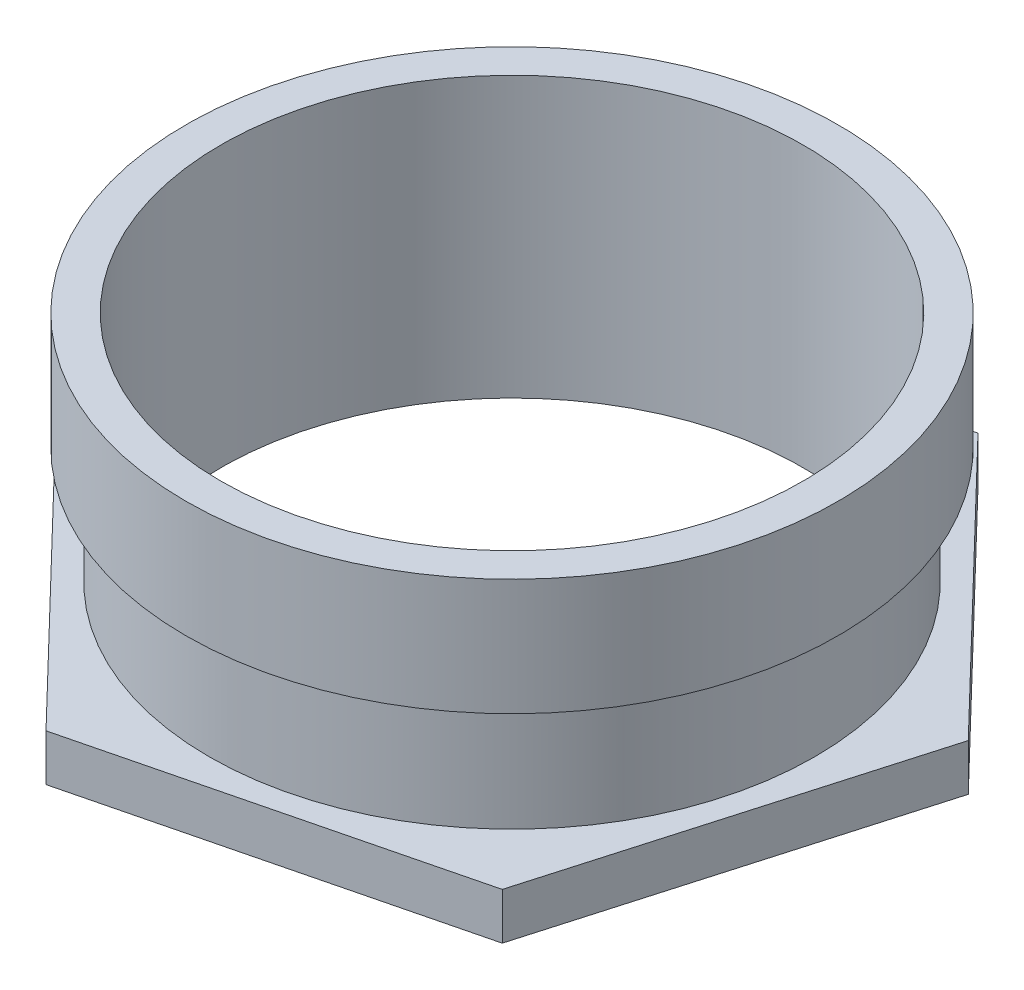
SolidWorks part; units mm, degrees
ref_plane "前基準面" through (0, 0, 0) normal (0, 0, 1) x (1, 0, 0)
ref_plane "上基準面" through (0, 0, 0) normal (0, 1, 0) x (1, 0, 0)
ref_plane "右基準面" through (0, 0, 0) normal (1, 0, 0) x (0, 0, -1)
sketch "草圖1" plane through (0, 0, 0) normal (0, 1, 0) x (1, 0, 0)
  line L0 (-4.469, -15.5358) -> (11.2199, -11.6382)
  line L6 (11.2199, -11.6382) -> (15.6889, 3.8977)
  line L7 (15.6889, 3.8977) -> (4.469, 15.5358)
  line L8 (4.469, 15.5358) -> (-11.2199, 11.6382)
  line L9 (-11.2199, 11.6382) -> (-15.6889, -3.8977)
  line L10 (-15.6889, -3.8977) -> (-4.469, -15.5358)
  circle A0 centre (0, 0) radius 14 construction
  circle A1 centre (0, 0) radius 12.5
  dimension "D1" = 25
extrude "填料-伸長1" add sketch "草圖1" along normal blind 2
sketch "草圖2" plane through (0, 2, 0) normal (0, 1, 0) x (1, 0, 0)
  circle A0 centre (0, 0) radius 12.5
  circle A1 centre (0, 0) radius 13
  dimension "D1" = 26
extrude "填料-伸長2" add sketch "草圖2" along normal blind 5
sketch "草圖3" plane through (0, 7, 0) normal (0, 1, 0) x (1, 0, 0)
  circle A0 centre (0, 0) radius 12.5
  circle A1 centre (0, 0) radius 14
  dimension "D1" = 28
extrude "填料-伸長3" add sketch "草圖3" along normal blind 5
